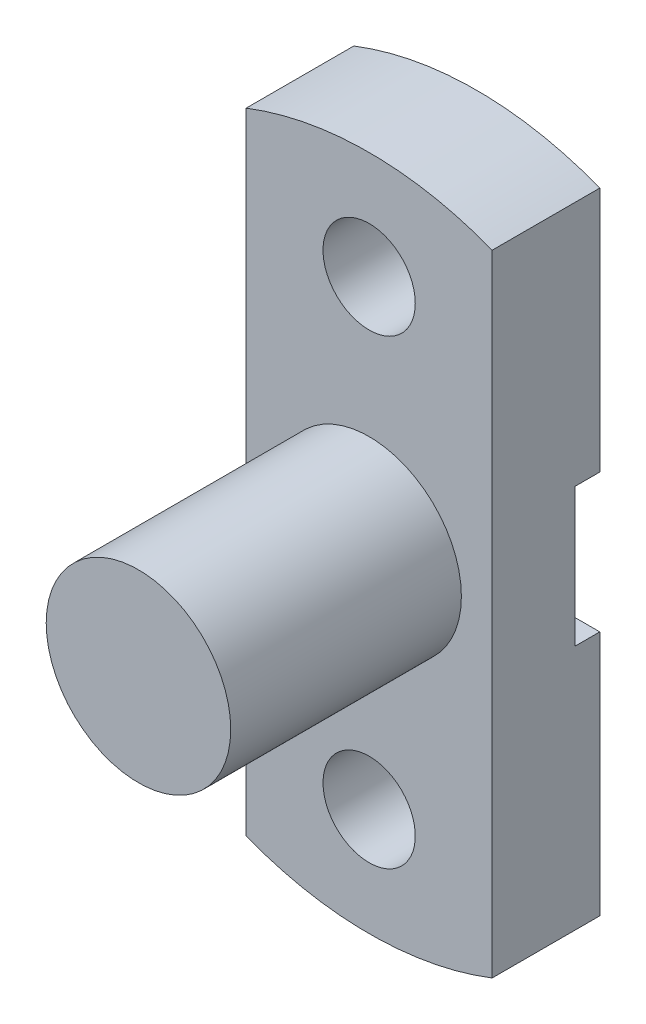
SolidWorks part; units mm, degrees
ref_plane "Front Plane" through (0, 0, 0) normal (0, 0, 1) x (1, 0, 0)
ref_plane "Top Plane" through (0, 0, 0) normal (0, 1, 0) x (1, 0, 0)
ref_plane "Right Plane" through (0, 0, 0) normal (1, 0, 0) x (0, 0, -1)
sketch "Sketch1" plane through (0, 0, 0) normal (0, 0, 1) x (1, 0, 0)
  line L0 (0, 110) -> (0, -110) construction
  line L1 (66.9074, 0) -> (-63.1375, 0) construction
  line L2 (-40, 102.4695) -> (-40, -102.4695)
  line L3 (40, 102.4695) -> (40, -102.4695)
  arc A0 (40, 102.4695) -> (-40, 102.4695) centre (0, 0) ccw
  circle A1 centre (0, 75) radius 15
  circle A3 centre (0, -75) radius 15
  arc A4 (-40, -102.4695) -> (40, -102.4695) centre (0, 0) ccw
  point P1 (38.152, -102.4695)
  dimension "D1" = 220
  dimension "D2" = 30
  dimension "D3" = 150
  dimension "D4" = 40
  dimension "D5" = 40
extrude "Boss-Extrude2" add sketch "Sketch1" along normal blind 35
sketch "Sketch2" plane through (0, 0, 35) normal (0, 0, 1) x (1, 0, 0)
  circle A0 centre (0, 0) radius 30
  dimension "D1" = 60
extrude "Boss-Extrude3" add sketch "Sketch2" along normal blind 75
sketch "Sketch3" plane through (-40, 0, 0) normal (-1, 0, 0) x (0, 0, 1)
  line L0 (0, 22.5) -> (8, 22.5)
  line L1 (0, 102.4695) -> (0, -102.4695) construction
  line L2 (8, 22.5) -> (8, -22.5)
  line L3 (8, -22.5) -> (0, -22.5)
  line L4 (0, -22.5) -> (0, 22.5)
  dimension "D1" = 22.5
  dimension "D2" = 22.5
  dimension "D3" = 8
extrude "Cut-Extrude1" cut sketch "Sketch3" against normal through all
